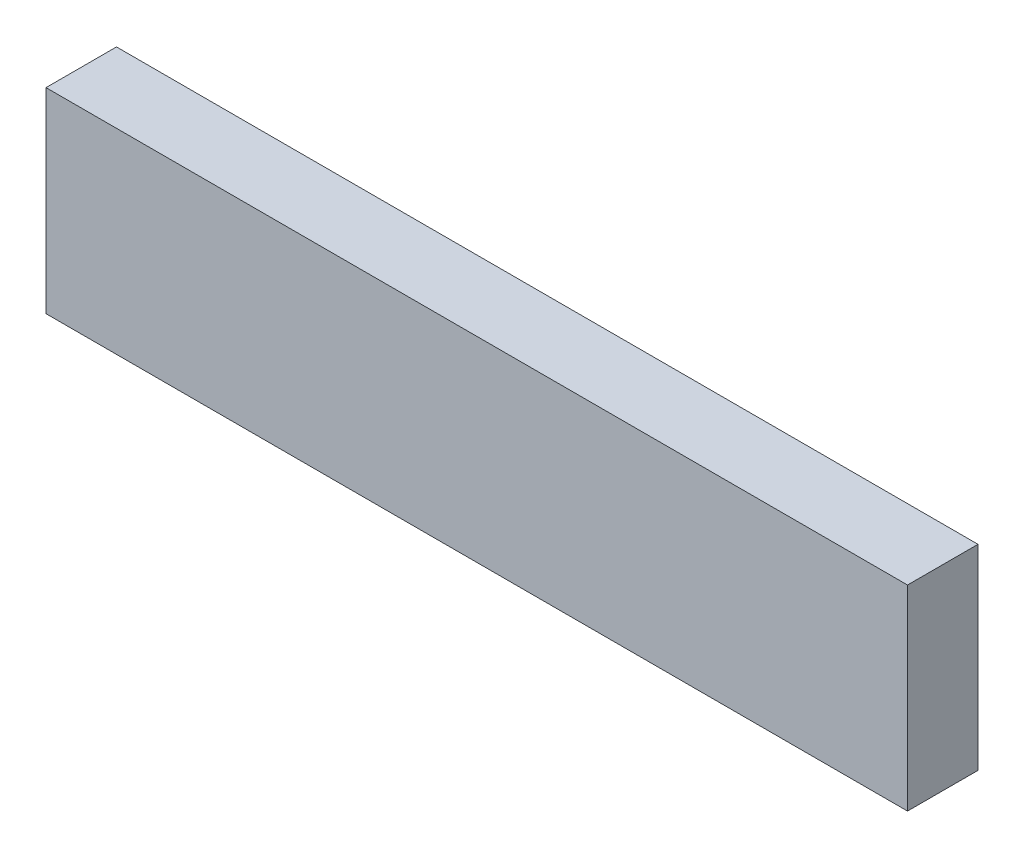
SolidWorks part; units mm, degrees
ref_plane "Front Plane" through (0, 0, 0) normal (0, 0, 1) x (1, 0, 0)
ref_plane "Top Plane" through (0, 0, 0) normal (0, 1, 0) x (1, 0, 0)
ref_plane "Right Plane" through (0, 0, 0) normal (1, 0, 0) x (0, 0, -1)
sketch "Sketch1" plane through (0, 0, 0) normal (0, 0, 1) x (1, 0, 0)
  line L1 (-110, -25) -> (110, -25)
  line L2 (-110, -25) -> (-110, 25)
  line L3 (-110, 25) -> (110, 25)
  line L4 (110, -25) -> (110, 25)
  line L5 (-110, -25) -> (110, 25) construction
  line L6 (-110, 25) -> (110, -25) construction
  point P0 (0, 0)
  dimension "D1" = 220
  dimension "D2" = 50
extrude "Boss-Extrude1" add sketch "Sketch1" along normal blind 18
